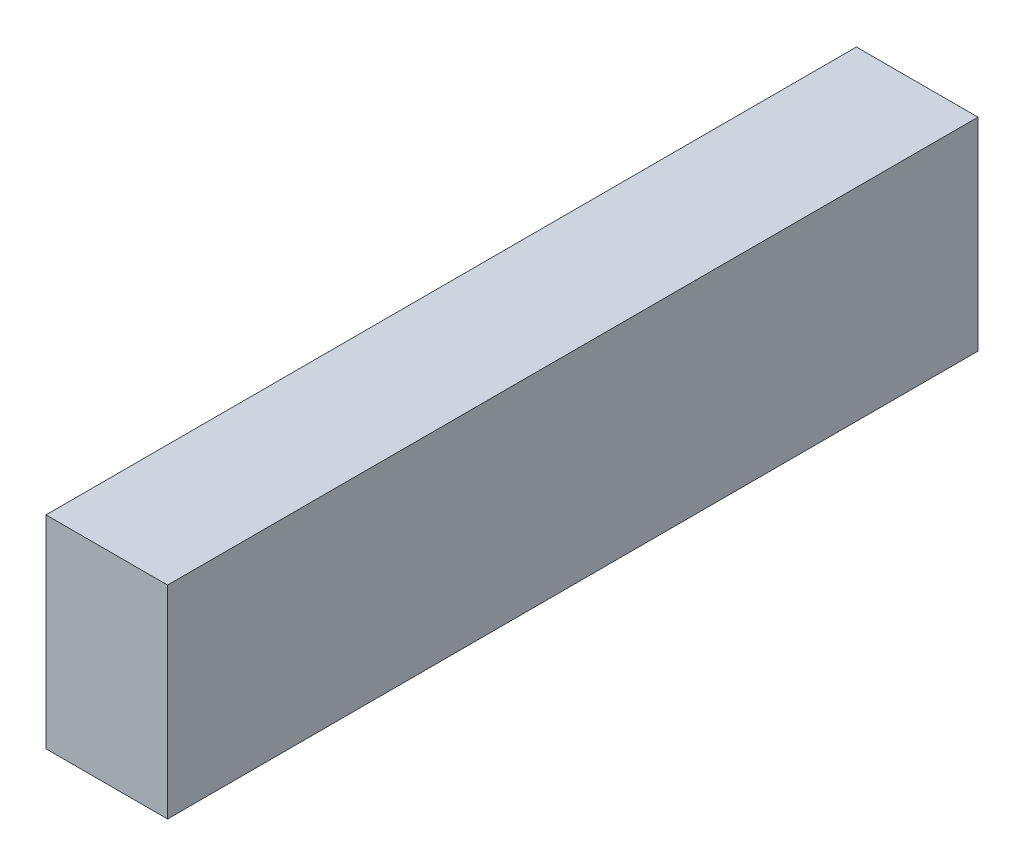
SolidWorks part; units mm, degrees
ref_plane "Front Plane" through (0, 0, 0) normal (0, 0, 1) x (1, 0, 0)
ref_plane "Top Plane" through (0, 0, 0) normal (0, 1, 0) x (1, 0, 0)
ref_plane "Right Plane" through (0, 0, 0) normal (1, 0, 0) x (0, 0, -1)
sketch "Sketch1" plane through (0, 0, 0) normal (0, 0, 1) x (1, 0, 0)
  line L1 (-15, 25) -> (15, 25)
  line L2 (-15, 25) -> (-15, -25)
  line L3 (-15, -25) -> (15, -25)
  line L4 (15, 25) -> (15, -25)
  line L5 (-15, 25) -> (15, -25) construction
  line L6 (-15, -25) -> (15, 25) construction
  point P0 (0, 0)
  dimension "D1" = 30
  dimension "D2" = 50
extrude "Boss-Extrude1" add sketch "Sketch1" along normal blind 200
